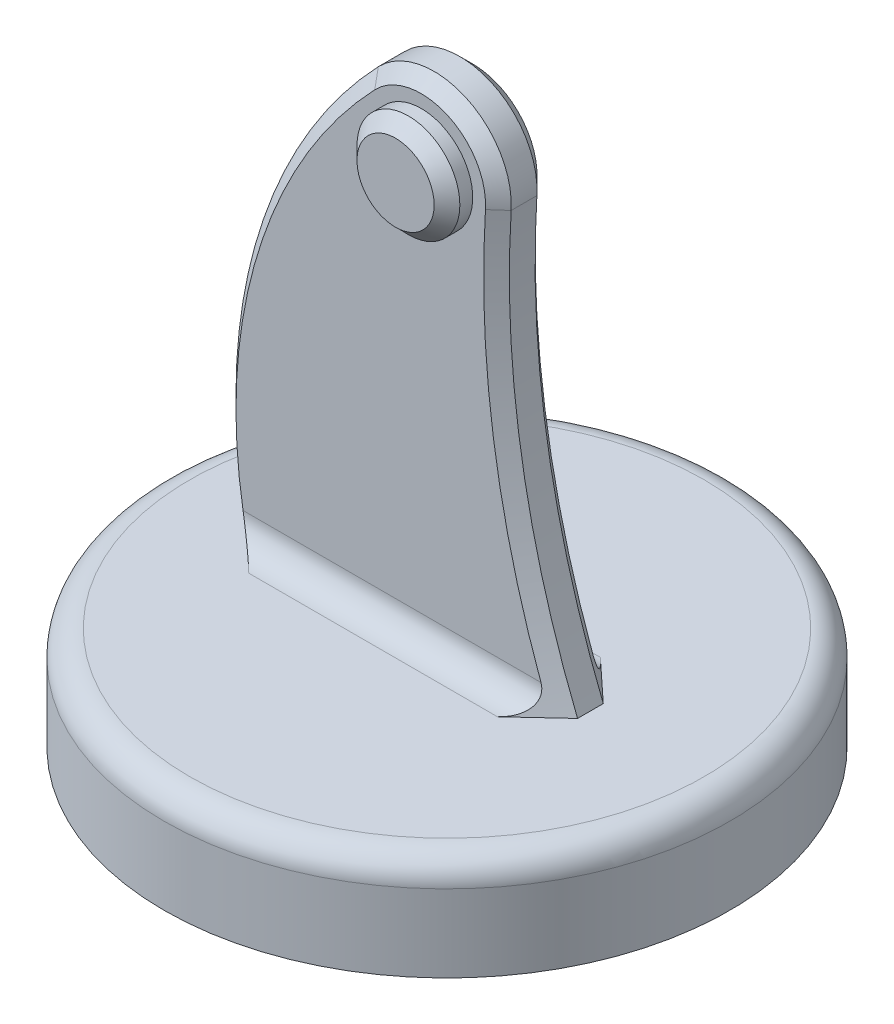
SolidWorks part; units mm, degrees
ref_plane "Front Plane" through (0, 0, 0) normal (0, 0, 1) x (1, 0, 0)
ref_plane "Top Plane" through (0, 0, 0) normal (0, 1, 0) x (1, 0, 0)
ref_plane "Right Plane" through (0, 0, 0) normal (1, 0, 0) x (0, 0, -1)
sketch "Sketch2" plane through (0, 0, 0) normal (0, 1, 0) x (1, 0, 0)
  circle A0 centre (0, 0) radius 55
  dimension "D1" = 110
extrude "Boss-Extrude1" add sketch "Sketch2" along normal blind 20
fillet "Fillet1" radius 5 1 edges at (0, 20, 55)
sketch "Sketch3" plane through (0, 0, 0) normal (0, 0, 1) x (1, 0, 0)
  line L0 (0, 0) -> (0, 100) construction
  line L1 (-55, 15) -> (55, 15) construction
  line L2 (-35, 15) -> (30, 15)
  arc A0 (14.9706, 99.062) -> (-10.8492, 110.3583) centre (0, 100) ccw
  arc A1 (-35, 15) -> (-10.8492, 110.3583) centre (61.4788, 41.3028) cw
  arc A2 (30, 15) -> (14.9706, 99.062) centre (194.6184, 87.8065) cw
  dimension "D4" = 30
  dimension "D5" = 180
  dimension "D6" = 100
  dimension "D1" = 30
  dimension "D2" = 35
  dimension "D3" = 100
extrude "Boss-Extrude2" add sketch "Sketch3" along normal mid plane 10
chamfer "Chamfer1" distance 2.5 angle 45 3 edges at (-34.7965, 68.3412, 5) (6.0123, 113.7423, 5) (16.9703, 58.8038, 5)
chamfer "Chamfer2" distance 2.5 angle 45 3 edges at (16.9703, 58.8038, -5) (6.0123, 113.7423, -5) (-34.7965, 68.3412, -5)
fillet "Fillet2" radius 5 2 edges at (-4.2415, 20, -5) (-4.2415, 20, 5)
sketch "Sketch4" plane through (0, 0, 5) normal (0, 0, 1) x (1, 0, 0)
  circle A0 centre (0, 100) radius 10
  dimension "D1" = 20
extrude "Boss-Extrude3" add sketch "Sketch4" along normal blind 5
chamfer "Chamfer3" distance 2.5 angle 45 1 edges at (10, 100, 10)
sketch "Sketch5" plane through (0, 0, -5) normal (0, 0, -1) x (-1, 0, 0)
  circle A0 centre (0, 100) radius 5
  dimension "D1" = 10
extrude "Cut-Extrude1" cut sketch "Sketch5" against normal blind 10
sketch "Sketch8" plane through (0, 0, 0) normal (0, -1, 0) x (1, 0, 0)
  circle A0 centre (0, 0) radius 50
extrude "Cut-Extrude2" cut sketch "Sketch8" against normal blind 15
